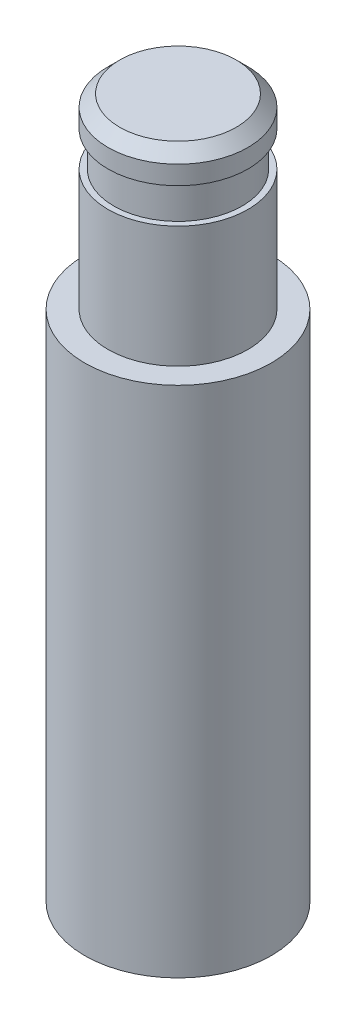
SolidWorks part; units mm, degrees
ref_plane "前视基准面" through (0, 0, 0) normal (0, 0, 1) x (1, 0, 0)
ref_plane "上视基准面" through (0, 0, 0) normal (0, 1, 0) x (1, 0, 0)
ref_plane "右视基准面" through (0, 0, 0) normal (1, 0, 0) x (0, 0, -1)
sketch "草图1" plane through (0, 0, 0) normal (0, 1, 0) x (1, 0, 0)
  circle A0 centre (0, 0) radius 4
  dimension "D1" = 8
extrude "凸台-拉伸1" add sketch "草图1" along normal mid plane 22
sketch "草图2" plane through (0, 11, 0) normal (0, 1, 0) x (1, 0, 0)
  circle A0 centre (0, 0) radius 3
  dimension "D1" = 6
extrude "凸台-拉伸2" add sketch "草图2" along normal blind 8
sketch "草图3" plane through (0, 11, 0) normal (0, 1, 0) x (1, 0, 0)
  circle A0 centre (0, 0) radius 2.75
  dimension "D1" = 5.5
extrude "切除-拉伸1" cut sketch "草图3" along normal blind 1.5 from offset 5.2 flip side to cut
chamfer "倒角1" distance 0.5 angle 45 1 edges at (0, 19, 3)
